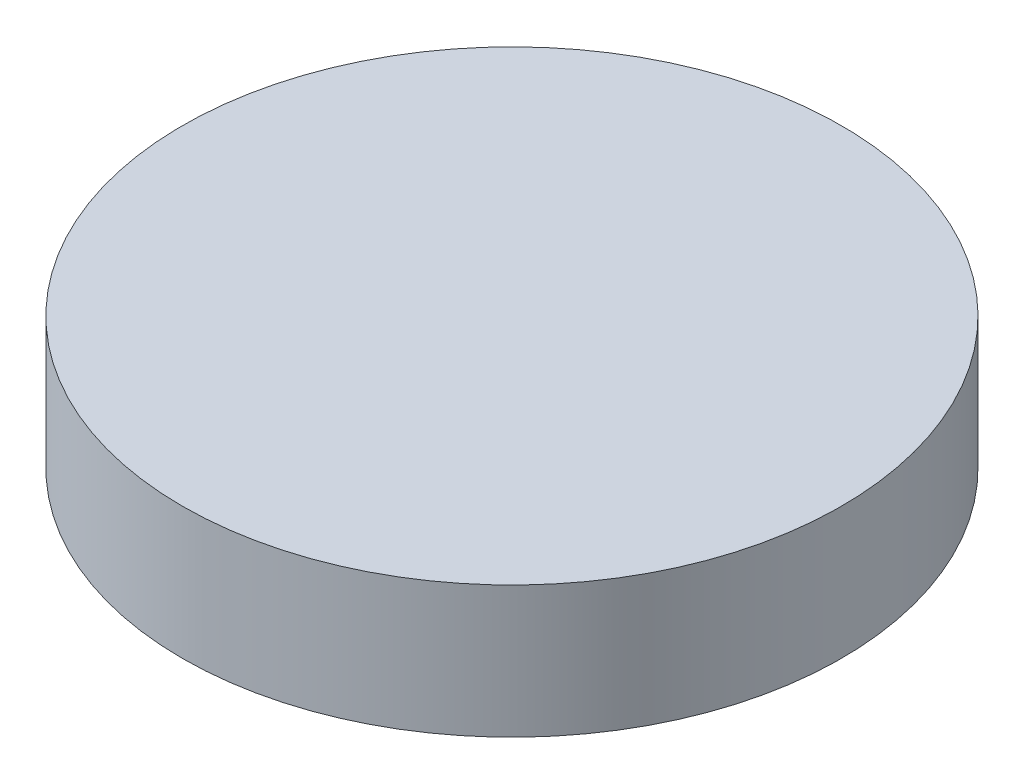
SolidWorks part; units mm, degrees
ref_plane "Front Plane" through (0, 0, 0) normal (0, 0, 1) x (1, 0, 0)
ref_plane "Top Plane" through (0, 0, 0) normal (0, 1, 0) x (1, 0, 0)
ref_plane "Right Plane" through (0, 0, 0) normal (1, 0, 0) x (0, 0, -1)
sketch "Sketch1" plane through (0, 0, 0) normal (0, 1, 0) x (1, 0, 0)
  circle A0 centre (0, 0) radius 330
  dimension "D1" = 660
extrude "Boss-Extrude1" add sketch "Sketch1" along normal blind 132
sketch "Sketch2" plane through (0, 0, 0) normal (0, -1, 0) x (1, 0, 0)
  line L0 (0, 330) -> (0, -330) construction
  line L1 (-330, 0) -> (330, 0) construction
  circle A0 centre (0, 0) radius 330 construction
sketch "Sketch3" plane through (0, 0, 0) normal (0, -1, 0) x (1, 0, 0)
  line L0 (25.9938, 2.0253) -> (329.9938, 2.0253) construction
  line L1 (25.9938, 2.0253) -> (25.9938, -328.9747) construction
  line L3 (-19.0062, -42.9747) -> (70.9938, -42.9747)
  line L4 (-19.0062, -42.9747) -> (-19.0062, 47.0253)
  line L5 (-19.0062, 47.0253) -> (70.9938, 47.0253)
  line L6 (70.9938, -42.9747) -> (70.9938, 47.0253)
  line L7 (-19.0062, -42.9747) -> (70.9938, 47.0253) construction
  line L8 (-19.0062, 47.0253) -> (70.9938, -42.9747) construction
  circle A0 centre (0, 0) radius 330 construction
  circle A1 centre (25.9938, 2.0253) radius 45 construction
  dimension "D3" = 90
  dimension "D1" = 331
  dimension "D2" = 304
extrude "Boss-Extrude2" add sketch "Sketch3" along normal blind 34
